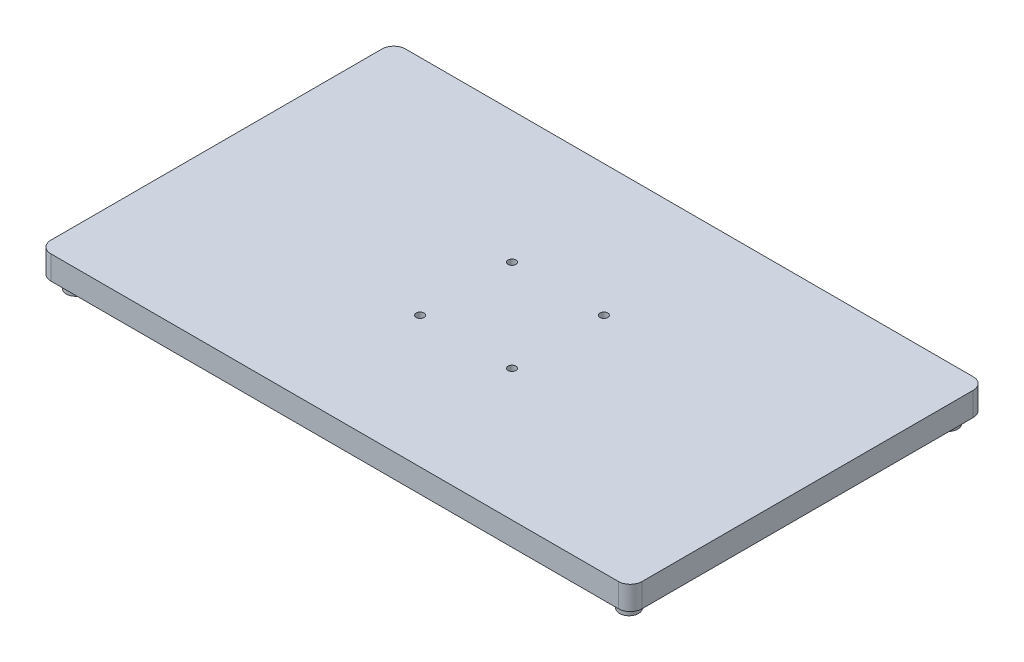
SolidWorks part; units mm, degrees
ref_plane "前视基准面" through (0, 0, 0) normal (0, 0, 1) x (1, 0, 0)
ref_plane "上视基准面" through (0, 0, 0) normal (0, 1, 0) x (1, 0, 0)
ref_plane "右视基准面" through (0, 0, 0) normal (1, 0, 0) x (0, 0, -1)
sketch "Sketch1" plane through (0, 0, 0) normal (0, 1, 0) x (1, 0, 0)
  line L1 (240, -150) -> (-240, -150)
  line L2 (250, -140) -> (250, 140)
  line L3 (240, 150) -> (-240, 150)
  line L4 (-250, -140) -> (-250, 140)
  line L5 (250, -150) -> (-250, 150) construction
  line L6 (250, 150) -> (-250, -150) construction
  arc A0 (-240, -150) -> (-250, -140) centre (-240, -140) cw
  arc A1 (250, -140) -> (240, -150) centre (240, -140) cw
  arc A2 (250, 140) -> (240, 150) centre (240, 140) ccw
  arc A3 (-240, 150) -> (-250, 140) centre (-240, 140) ccw
  point P0 (0, 0)
  dimension "D3" = 10
  dimension "D1" = 500
  dimension "D2" = 300
extrude "Boss-Extrude1" add sketch "Sketch1" along normal blind 20
sketch "Sketch2" plane through (0, 0, 0) normal (0, 1, 0) x (1, 0, 0)
  line L5 (38.87, 38.87) -> (-38.87, 38.87) construction
  line L6 (38.87, 38.87) -> (38.87, -38.87) construction
  line L7 (38.87, -38.87) -> (-38.87, -38.87) construction
  line L8 (-38.87, 38.87) -> (-38.87, -38.87) construction
  line L9 (38.87, 38.87) -> (-38.87, -38.87) construction
  line L10 (38.87, -38.87) -> (-38.87, 38.87) construction
  circle A9 centre (-38.87, -38.87) radius 3.3
  circle A10 centre (38.87, -38.87) radius 3.3
  circle A11 centre (38.87, 38.87) radius 3.3
  circle A12 centre (-38.87, 38.87) radius 3.3
  point P0 (0, 0)
  dimension "D3" = 6.6
  dimension "D1" = 77.74
  dimension "D2" = 77.74
extrude "Cut-Extrude2" cut sketch "Sketch2" along normal blind 20 and the other way through all
sketch "Sketch3" plane through (0, 0, 0) normal (0, 1, 0) x (1, 0, 0)
  line L1 (234, -135) -> (-234, -135) construction
  line L2 (234, -135) -> (234, 135) construction
  line L3 (234, 135) -> (-234, 135) construction
  line L4 (-234, -135) -> (-234, 135) construction
  line L5 (234, -135) -> (-234, 135) construction
  line L6 (234, 135) -> (-234, -135) construction
  circle A0 centre (-234, 135) radius 8
  circle A1 centre (234, 135) radius 8
  circle A2 centre (234, -135) radius 8
  circle A3 centre (-234, -135) radius 8
  point P0 (0, 0)
  dimension "D3" = 16
  dimension "D1" = 270
  dimension "D2" = 468
  dimension "D4" = 2
extrude "Boss-Extrude2" add sketch "Sketch3" against normal blind 10
